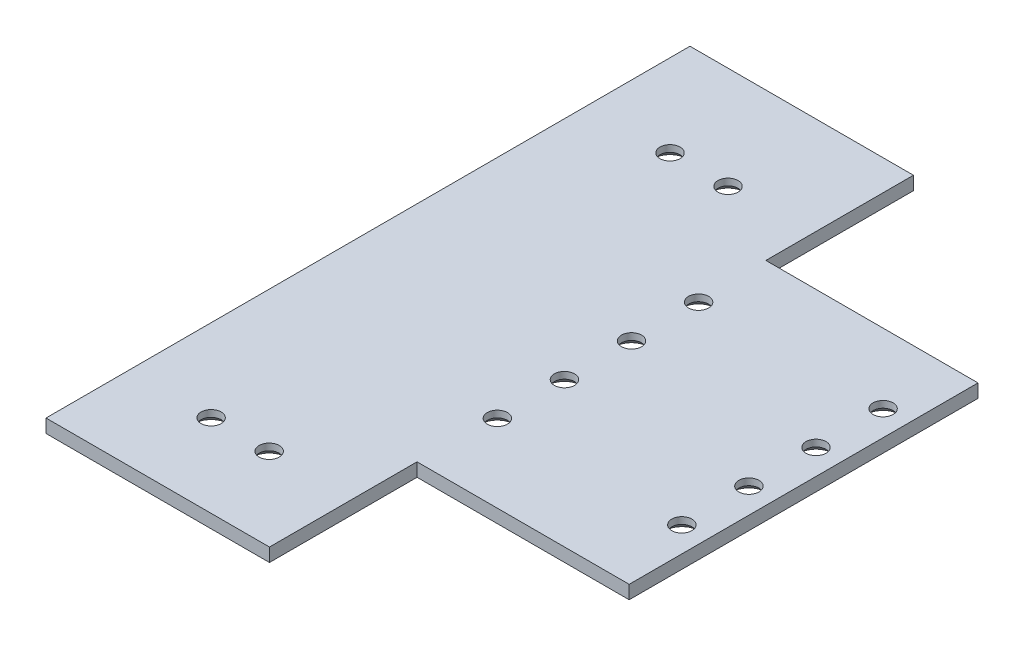
SolidWorks part; units mm, degrees
ref_plane "Спереди" through (0, 0, 0) normal (0, 0, 1) x (1, 0, 0)
ref_plane "Сверху" through (0, 0, 0) normal (0, 1, 0) x (1, 0, 0)
ref_plane "Справа" through (0, 0, 0) normal (1, 0, 0) x (0, 0, -1)
sketch "Эскиз1" plane through (0, 0, 0) normal (0, 1, 0) x (1, 0, 0)
  line L5 (49.9338, 26) -> (18.3099, 26)
  line L6 (49.9338, 26) -> (49.9338, -26)
  line L7 (49.9338, -26) -> (18.3099, -26)
  line L8 (-48.9591, 48) -> (15, 48)
  line L9 (-48.9591, 48) -> (-48.9591, -48)
  line L10 (-50, 0) -> (49.9338, 0) construction
  line L11 (-48.9591, -48) -> (15, -48)
  line L12 (-45.2656, -36.9305) -> (-45.2656, -25.3095)
  line L13 (-45.2656, 36.9305) -> (-27.3726, 36.9305)
  line L14 (-45.2656, 36.9305) -> (-45.2656, 25.3095)
  line L15 (-45.2656, 25.3095) -> (-27.3726, 25.3095)
  line L16 (-27.3726, 36.9305) -> (-27.3726, 25.3095)
  line L21 (-45.2656, -25.3095) -> (-27.3726, -25.3095)
  line L22 (-27.3726, -36.9305) -> (-27.3726, -25.3095)
  line L23 (-45.2656, -36.9305) -> (-27.3726, -36.9305)
  line L24 (-15.0662, -48) -> (20.6445, -48) construction
  line L27 (15, -48) -> (18.3099, -48)
  line L28 (18.3099, -26) -> (18.3099, -48)
  line L29 (15, 48) -> (18.3099, 48)
  line L30 (18.3099, 26) -> (18.3099, 48)
  line L31 (19.3099, 31) -> (19.3099, 26) construction
  line L32 (17.5113, 27.0025) -> (47.3563, 27.0025) construction
  dimension "D1" = 1
  dimension "D2" = 1.0025
extrude "Бобышка-Вытянуть1" add sketch "Эскиз1" along normal blind 2
sketch "Эскиз2" plane through (0, 2, 0) normal (0, 1, 0) x (1, 0, 0)
  circle A0 centre (46.1838, -14.4) radius 1.5
  circle A1 centre (18.6838, -14.4) radius 1.5
  circle A2 centre (18.6838, -4.4) radius 1.5
  circle A3 centre (46.1838, -4.4) radius 1.5
  circle A4 centre (18.6838, 5.6) radius 1.5
  circle A5 centre (46.1838, 5.6) radius 1.5
  circle A6 centre (18.6838, 15.6) radius 1.5
  circle A7 centre (46.1838, 15.6) radius 1.5
  dimension "D1" = 4
extrude "Вырез-Вытянуть1" cut sketch "Эскиз2" against normal blind 10
chamfer "Фаска1" distance 1 angle 45 8 edges at (18.6838, 0, -17.1) (18.6838, 0, -7.1) (18.6838, 0, 2.9) (18.6838, 0, 12.9) (46.1838, 0, -17.1) (46.1838, 0, -7.1) (46.1838, 0, 2.9) (46.1838, 0, 12.9)
sketch "Эскиз3" plane through (0, 2, 0) normal (0, 1, 0) x (1, 0, 0)
  circle A0 centre (5.9236, 32.747) radius 1.5
  circle A1 centre (-2.7264, 32.747) radius 1.5
  circle A2 centre (-2.7264, -35.6602) radius 1.5
  circle A3 centre (5.9236, -35.6602) radius 1.5
extrude "Вырез-Вытянуть2" cut sketch "Эскиз3" against normal blind 10
sketch "Эскиз4" plane through (0, 2, 0) normal (0, 1, 0) x (1, 0, 0)
  line L0 (49.9338, 26) -> (49.9338, -48) construction
  line L1 (-48.9591, -48) -> (15, -48) construction
  line L2 (15, -48) -> (49.9338, -48) construction
  line L3 (18.3099, 48) -> (-48.9591, 48) construction
  line L9 (-48.9591, 48) -> (-15.0021, 48)
  line L10 (-48.9591, 48) -> (-48.9591, -48)
  line L11 (-48.9591, -48) -> (-15.0021, -48)
  line L12 (-15.0021, 48) -> (-15.0021, -48)
extrude "Вырез-Вытянуть3" cut sketch "Эскиз4" against normal blind 10
chamfer "Фаска2" distance 1 angle 45 4 edges at (-2.7264, 0, 34.1602) (5.9236, 0, 34.1602) (-2.7264, 0, -34.247) (5.9236, 0, -34.247)
